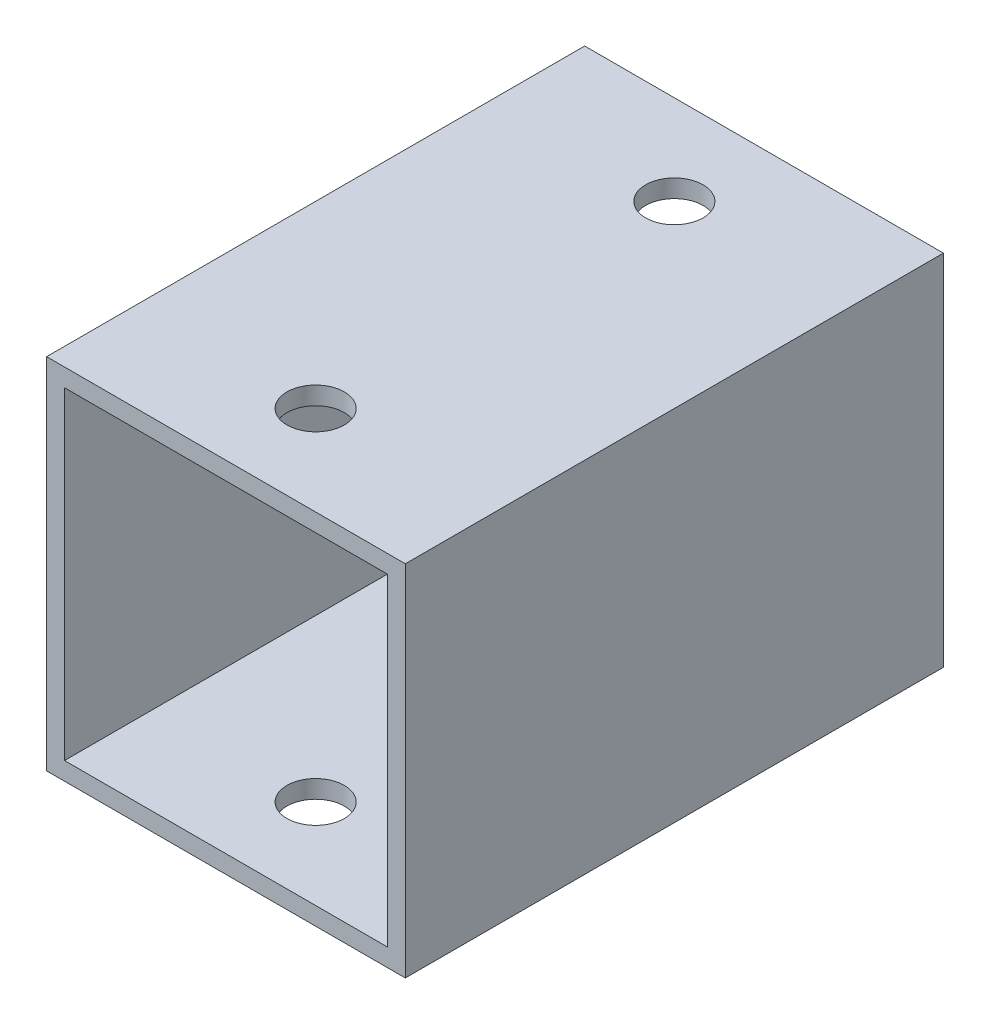
SolidWorks part; units mm, degrees
ref_plane "前视基准面" through (0, 0, 0) normal (0, 0, 1) x (1, 0, 0)
ref_plane "上视基准面" through (0, 0, 0) normal (0, 1, 0) x (1, 0, 0)
ref_plane "右视基准面" through (0, 0, 0) normal (1, 0, 0) x (0, 0, -1)
other "Configuration Table"
sketch "草图1" plane through (0, 0, 0) normal (0, 0, 1) x (1, 0, 0)
  line L1 (-9, 9) -> (9, 9)
  line L2 (-9, 9) -> (-9, -9)
  line L3 (-9, -9) -> (9, -9)
  line L4 (9, 9) -> (9, -9)
  line L5 (-9, 9) -> (9, -9) construction
  line L6 (-9, -9) -> (9, 9) construction
  line L7 (-10, 10) -> (10, 10)
  line L8 (-10, 10) -> (-10, -10)
  line L9 (-10, -10) -> (10, -10)
  line L10 (10, 10) -> (10, -10)
  line L11 (-10, 10) -> (10, -10) construction
  line L12 (-10, -10) -> (10, 10) construction
  point P0 (0, 0)
  point P6 (0, 0)
  dimension "D1" = 20
  dimension "D2" = 20
  dimension "D3" = 1
  dimension "D4" = 1
extrude "凸台-拉伸1" add sketch "草图1" along normal blind 30
sketch "草图2" plane through (0, 10, 0) normal (0, 1, 0) x (1, 0, 0)
  line L0 (0, 0) -> (0, -30) construction
  line L1 (10, 0) -> (-10, 0) construction
  line L2 (10, -30) -> (-10, -30) construction
  circle A0 centre (0, -5) radius 1.6
  circle A1 centre (0, -25) radius 1.6
  dimension "D3" = 3.2
  dimension "D1" = 20
  dimension "D2" = 5
extrude "切除-拉伸1" cut sketch "草图2" against normal blind 50
